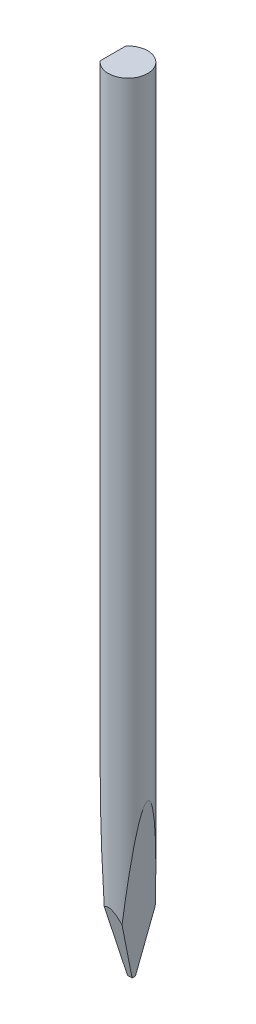
SolidWorks part; units mm, degrees
material "Tungsten"
ref_plane "Front Plane" through (0, 0, 0) normal (0, 0, 1) x (1, 0, 0)
ref_plane "Top Plane" through (0, 0, 0) normal (0, 1, 0) x (1, 0, 0)
ref_plane "Right Plane" through (0, 0, 0) normal (1, 0, 0) x (0, 0, -1)
sketch "TD_sketch" plane through (0, 0, 0) normal (0, 1, 0) x (1, 0, 0)
  circle A0 centre (0, 0) radius 1.5862
  dimension "TD" = 3.1725
extrude "TL_feature" add sketch "TD_sketch" along normal blind 63.5
sketch "TDF_sketch" plane through (0, 0, 0) normal (0, 1, 0) x (1, 0, 0)
  line L0 (-1.2078, 0) -> (1.5862, 0) construction
  line L1 (-1.2078, -1.5962) -> (-4.4002, -1.5962)
  line L2 (-1.2078, -1.5962) -> (-1.2078, 1.5962)
  line L3 (-1.2078, 1.5962) -> (-4.4002, 1.5962)
  line L4 (-4.4002, -1.5962) -> (-4.4002, 1.5962)
  line L5 (-1.2078, -1.5962) -> (-4.4002, 1.5962) construction
  line L6 (-1.2078, 1.5962) -> (-4.4002, -1.5962) construction
  circle A0 centre (0, 0) radius 1.5862 construction
  point P3 (-2.804, 0)
  dimension "TD" = 3.1725
  dimension "TDF" = 2.794
  dimension "Offset" = 3.1925
extrude "TDF_feature" cut sketch "TDF_sketch" along normal through all
sketch "ISA_sketch" plane through (0, 0, 0) normal (1, 0, 0) x (0, 0, -1)
  line L0 (-1.5862, 0) -> (1.5862, 0) construction
  line L1 (0, 0) -> (0, 63.5) construction
  line L2 (-0.1333, 0) -> (0.1333, 0)
  line L3 (0.1333, 0) -> (17.1481, 63.5)
  line L4 (-0.1333, 0) -> (-17.1481, 63.5)
  dimension "TD" = 3.1725
  dimension "TL" = 63.5
  dimension "W" = 0.2667
  dimension "ISA" = 30
extrude "ISA_feature" cut sketch "ISA_sketch" against normal through all both and the other way through all
sketch "VR_sketch" [suppressed] plane through (0, 0, 0) normal (1, 0, 0) x (0, 0, -1)
  line L0 (-1.5862, 0) -> (1.5862, 0) construction
  line L1 (0, 0) -> (0, 63.5) construction
  line L2 (-0.4483, 0) -> (0.4483, 0)
  line L3 (0.4483, 0) -> (0.4483, 1.016)
  line L4 (0.4855, 1.1058) -> (62.8797, 63.5)
  line L5 (-0.4855, 1.1058) -> (-62.8797, 63.5)
  line L6 (-0.4483, 0) -> (-0.4483, 1.016)
  arc A0 (0.4483, 1.016) -> (0.4855, 1.1058) centre (0.5753, 1.016) cw
  arc A1 (-0.4483, 1.016) -> (-0.4855, 1.1058) centre (-0.5753, 1.016) ccw
  dimension "TD" = 3.1725
  dimension "TL" = 63.5
  dimension "VRR" = 0.127
  dimension "VR" = 1.016
  dimension "VW" = 0.8966
  dimension "VRA" = 90
extrude "VR_feature" [suppressed] cut sketch "VR_sketch" against normal through all both and the other way through all
sketch "STD_shank_sketch" plane through (0, 0, 0) normal (0, 0, 1) x (1, 0, 0)
  line L0 (-1.5862, 0) -> (1.5862, 0) construction
  line L1 (-1.2078, 0) -> (-1.2078, 63.5) construction
  line L2 (0.4636, 0) -> (0.4636, 63.5) construction
  line L3 (0.4636, 0) -> (6.0191, 63.5)
  line L4 (0.4636, 0) -> (0.0953, 0)
  line L5 (0.0953, 0) -> (-5.4603, 63.5)
  dimension "TD" = 3.1725
  dimension "TL" = 63.5
  dimension "TDF" = 2.794
  dimension "X" = 1.1227
  dimension "BA" = 5
  dimension "FA" = 5
  dimension "FL" = 0.3683
extrude "STD_shank_feature" cut sketch "STD_shank_sketch" against normal through all both and the other way through all
sketch "VFL_sketch" [suppressed] plane through (0, 0, 0) normal (0, 0, 1) x (1, 0, 0)
  line L0 (-1.5862, 0) -> (1.5862, 0) construction
  line L1 (-1.2078, 0) -> (-1.2078, 63.5) construction
  line L2 (0.6083, 0) -> (0.6083, 63.5) construction
  line L3 (-0.2299, 0) -> (-0.2299, 1.905)
  line L4 (-0.2376, 1.9932) -> (-11.0829, 63.5)
  arc A0 (-0.2299, 1.905) -> (-0.2376, 1.9932) centre (-0.7379, 1.905) ccw
  dimension "TD" = 3.1725
  dimension "TL" = 63.5
  dimension "TDF" = 2.794
  dimension "X" = 1.1227
  dimension "FL" = 0.3683
  dimension "VFLR" = 0.508
  dimension "VFL" = 1.905
  dimension "angle" = 10
extrude "VFL_feature" [suppressed] cut sketch "VFL_sketch" against normal through all both and the other way through all
sketch "G_groove_sketch" [suppressed] plane through (0, 0, 0) normal (1, 0, 0) x (0, 0, -1)
  line L0 (-1.5862, 0) -> (1.5862, 0) construction
  line L1 (0, 0) -> (0, 63.5) construction
  line L2 (0.0229, 0.0689) -> (0.0711, 0)
  line L3 (0.0711, 0) -> (-0.0711, 0)
  line L4 (-0.0711, 0) -> (-0.0229, 0.0689)
  arc A0 (0.0229, 0.0689) -> (-0.0229, 0.0689) centre (0, 0.0529) ccw
  dimension "TD" = 3.1725
  dimension "TL" = 63.5
  dimension "GR" = 0.0279
  dimension "GA" = 70
  dimension "B" = 0.1422
extrude "G_groove_feature" [suppressed] cut sketch "G_groove_sketch" against normal through all both and the other way through all
sketch "FR_BR_STD_sketch" [suppressed] plane through (0, 0, 0) normal (0, 0, 1) x (1, 0, 0)
  line L0 (0.0953, 0) -> (-5.4603, 63.5) construction
  line L1 (0.4636, 0) -> (6.0191, 63.5) construction
  line L2 (0.1411, 0.0813) -> (0.3316, 0.0813)
  line L3 (-1.5862, 0) -> (1.5862, 0) construction
  arc A0 (0.0852, 0.1146) -> (0.1411, 0.0813) centre (0.1411, 0.1448) ccw
  arc A1 (0.484, 0.2337) -> (0.3316, 0.0813) centre (0.3316, 0.2337) cw
  dimension "BR" = 0.1524
  dimension "FR" = 0.0635
  dimension "GD" = 0.0813
  dimension "FRX" = 0.0559
  dimension "BRX" = 0.1524
surface "FR_BR_STD_feature" [suppressed]
sketch "G_groove_sketch<2>" [suppressed]
  dimension "TD" = 3.1725
  dimension "TL" = 63.5
  dimension "GR" = 0.0279
  dimension "GA" = 70
  dimension "B" = 0.1422
other "FR_BR_STD_cut_feature" [suppressed]
sketch "FR_BR_STD_VFL_sketch" [suppressed] plane through (0, 0, 0) normal (0, 0, 1) x (1, 0, 0)
  line L0 (-0.2299, 0) -> (-0.2299, 1.905) construction
  line L2 (0.2781, 0.3734) -> (0.1774, 0.3734)
  line L3 (0.6083, 0) -> (6.1639, 63.5) construction
  line L4 (0.6083, 0) -> (-0.2299, 0) construction
  arc A0 (-0.2299, 0.8814) -> (0.2781, 0.3734) centre (0.2781, 0.8814) ccw
  arc A1 (0.1774, 0.3734) -> (0.6854, 0.8814) centre (0.1774, 0.8814) ccw
  dimension "BR" = 0.1524
  dimension "FR" = 0.0635
  dimension "GD" = 0.0813
  dimension "FRX" = 0.0559
  dimension "BRX" = 0.1524
surface "FR_BR_STD_VFL_feature" [suppressed]
sketch "G_groove_sketch<3>" [suppressed]
  dimension "TD" = 3.1725
  dimension "TL" = 63.5
  dimension "GR" = 0.0279
  dimension "GA" = 70
  dimension "B" = 0.1422
other "FR_BR_STD_VFL_cut_feature" [suppressed]
sketch "FL_STD_sketch" [suppressed] plane through (0, 0, 0) normal (0, 0, 1) x (1, 0, 0)
  line L0 (0.0953, 0) -> (-5.4603, 63.5) construction
  line L1 (0.4636, 0) -> (6.0191, 63.5) construction
  line L2 (0.1411, 0.0813) -> (0.3316, 0.0813)
  line L3 (0.4636, 0) -> (0.0953, 0) construction
  arc A0 (0.0852, 0.1146) -> (0.1411, 0.0813) centre (0.1411, 0.1448) ccw
  arc A1 (0.484, 0.2337) -> (0.3316, 0.0813) centre (0.3316, 0.2337) cw
  dimension "BR" = 0.1524
  dimension "FR" = 0.0635
  dimension "GD" = 0.0813
  dimension "FRX" = 0.0559
  dimension "BRX" = 0.1524
sketch "FL_STD_VFL_sketch" [suppressed] plane through (0, 0, 0) normal (0, 0, 1) x (1, 0, 0)
  line L0 (-0.2299, 0) -> (-0.2299, 1.905) construction
  line L1 (0.6083, 0) -> (6.1639, 63.5) construction
  line L2 (0.2781, 0.3734) -> (0.1774, 0.3734)
  line L3 (-1.5862, 0) -> (1.5862, 0) construction
  arc A0 (-0.2299, 0.8814) -> (0.2781, 0.3734) centre (0.2781, 0.8814) ccw
  arc A1 (0.6854, 0.8814) -> (0.1774, 0.3734) centre (0.1774, 0.8814) cw
  dimension "BR" = 0.1524
  dimension "FR" = 0.0635
  dimension "GD" = 0.0813
  dimension "FRX" = 0.0559
  dimension "BRX" = 0.1524
sketch "TIP_sketch" [suppressed] plane through (0, 0, 0) normal (0, 0, 1) x (1, 0, 0)
  line L0 (-0.0113, 0.0339) -> (0.0321, 0.0339)
  line L1 (-0.0083, 0) -> (-0.2271, 2.5) construction
  line L2 (0.0291, 0) -> (0.2479, 2.5) construction
  line L3 (0.0291, 0) -> (-0.0083, 0) construction
  dimension "TIP" = 0.0339
sketch "ref_point" [suppressed] plane through (0, 0, 0) normal (1, 0, 0) x (0, 0, -1)
  point P0 (0, 0.2792)
  dimension "ref_point" = 0.2792
ref_plane "H_cut_plan" [suppressed] through (0, 0.2792, 0) normal (0, 1, 0) x (1, 0, 0)
other "H_cut_feature" [suppressed]
sketch "FG_FL_STD_overlay_sketch" [suppressed] plane through (0, 0, 0) normal (0, 0, 1) x (1, 0, 0)
  line L0 (0.4636, 0) -> (6.0191, 63.5) construction
  line L1 (0.4636, 0) -> (0.0953, 0) construction
  line L2 (0.0953, 0) -> (-5.4603, 63.5) construction
  line L3 (0.4636, 0) -> (0.488, 0.2792)
  line L4 (0.4636, 0) -> (0.0953, 0)
  line L5 (0.0953, 0) -> (0.0708, 0.2792)
  line L6 (0.0708, 0.2792) -> (0.488, 0.2792)
  line L7 (0.0406, 0.2792) -> (-0.0406, 0.2792) construction
  line L8 (0.4645, -0.0001) -> (0.489, 0.2791)
  line L9 (0.4626, 0.0001) -> (0.487, 0.2793)
  dimension "FL_UTOL" = 0.001
  dimension "FL_LTOL" = 0.001
sketch "FG_FL_STD_VFL_overlay_sketch" [suppressed] plane through (0, 0, 0) normal (0, 0, 1) x (1, 0, 0)
  line L0 (-0.0087, 0.0785) -> (-0.4356, 2.5) construction
  line L1 (0.0291, 0) -> (0.2479, 2.5) construction
  line L2 (0.0291, 0) -> (-0.0083, 0) construction
  line L3 (-0.0083, 0) -> (-0.0083, 0.075) construction
  line L4 (-0.0087, 0.0785) -> (-0.0314, 0.2077)
  line L5 (0.0291, 0) -> (0.0473, 0.2077)
  line L6 (0.0291, 0) -> (-0.0083, 0)
  line L7 (-0.0083, 0) -> (-0.0083, 0.075)
  line L8 (-0.0314, 0.2077) -> (0.0473, 0.2077)
  line L9 (0.0687, 0.2077) -> (-0.0687, 0.2077) construction
  line L10 (0.0301, -0.0001) -> (0.0483, 0.2076)
  line L11 (0.0282, 0.0001) -> (0.0463, 0.2078)
  arc A0 (-0.0083, 0.075) -> (-0.0087, 0.0785) centre (-0.0284, 0.075) ccw construction
  arc A1 (-0.0083, 0.075) -> (-0.0087, 0.0785) centre (-0.0284, 0.075) ccw
  dimension "FL_UTOL" = 0.001
  dimension "FL_LTOL" = 0.001
sketch "FG_B_STD_overlay_sketch" [suppressed] plane through (0, 0, 0) normal (1, 0, 0) x (0, 0, -1)
  line L0 (0.1333, 0) -> (17.1481, 63.5) construction
  line L1 (-0.1333, 0) -> (0.1333, 0) construction
  line L2 (-0.1333, 0) -> (-17.1481, 63.5) construction
  line L3 (0.1333, 0) -> (0.2082, 0.2792)
  line L4 (-0.1333, 0) -> (-0.0699, 0)
  line L5 (-0.1333, 0) -> (-0.2082, 0.2792)
  line L8 (0.0699, 0) -> (0.1333, 0)
  line L9 (-0.2082, 0.2792) -> (0.2082, 0.2792)
  line L10 (0.0221, 0.0683) -> (0.0703, -0.0006)
  line L11 (-0.0703, -0.0006) -> (-0.0221, 0.0683)
  line L12 (0.0221, 0.0683) -> (0.0699, 0)
  line L13 (-0.0699, 0) -> (-0.0221, 0.0683)
  line L14 (0.0237, 0.0695) -> (0.0719, 0.0006)
  line L15 (-0.0719, 0.0006) -> (-0.0237, 0.0695)
  line L16 (0.0237, 0.0695) -> (0.0723, 0)
  line L17 (-0.0723, 0) -> (-0.0237, 0.0695)
  line L18 (0.0406, 0.2792) -> (-0.0406, 0.2792) construction
  line L19 (-0.1324, 0.0003) -> (-0.2072, 0.2795)
  line L20 (-0.1343, -0.0003) -> (-0.2091, 0.279)
  arc A2 (0.0221, 0.0683) -> (-0.0221, 0.0683) centre (0, 0.0529) ccw
  arc A3 (0.0221, 0.0683) -> (-0.0221, 0.0683) centre (0, 0.0529) ccw
  arc A4 (0.0237, 0.0695) -> (-0.0237, 0.0695) centre (0, 0.0529) ccw
  arc A5 (0.0237, 0.0695) -> (-0.0237, 0.0695) centre (0, 0.0529) ccw
  ellipse E0 centre (1.3138, -1.5083) end of major axis (2.5414, -3.248) minor radius 0.1522 (0.105, 0.1264) -> (0.1442, 0.0406) ccw construction
  ellipse E1 centre (-1.3138, -1.5083) end of major axis (-0.0863, 0.2315) minor radius 0.1522 (-0.1442, 0.0406) -> (-0.105, 0.1264) ccw construction
  ellipse E2 centre (1.3138, -1.5083) end of major axis (2.5414, -3.248) minor radius 0.1522 (0.105, 0.1264) -> (0.1442, 0.0406) ccw
  ellipse E3 centre (-1.3138, -1.5083) end of major axis (-0.0863, 0.2315) minor radius 0.1522 (-0.1442, 0.0406) -> (-0.105, 0.1264) ccw
  spline S0 degree 3 poles (1644.6812, -1137.5783) (-11.5572, -22.4368) (-1.1514, 0.547) (0.0233, 0.2038) (0.035, 0.2004) (0.0462, 0.1946) (0.0562, 0.1876) (0.0688, 0.1788) (0.0799, 0.1677) (0.0889, 0.1552) (1.1453, -1.3082) (-25.0391, -24.8112) (-1139.1293, 1643.7059) knots -0.003641 -0.003641 -0.003641 -0.003641 0.000029 0.000029 0.000029 0.000066 0.000066 0.000066 0.000112 0.000112 0.000112 0.005548 0.005548 0.005548 0.005548 only from (0, 0.2072) to (0.105, 0.1264) construction
  spline S1 degree 3 poles (1108.6293, 1664.4054) (26.4709, -22.8226) (-1.0637, -1.3693) (-0.0934, 0.1486) (-0.085, 0.1618) (-0.0743, 0.1737) (-0.062, 0.1833) (-0.052, 0.1911) (-0.0408, 0.1977) (-0.0289, 0.202) (-0.02, 0.2051) (-0.0106, 0.2071) (-0.0012, 0.2072) (1.2104, 0.2251) (2.9491, -28.0575) (-1994.1481, -150.3085) knots -0.005313 -0.005313 -0.005313 -0.005313 0.000089 0.000089 0.000089 0.000136 0.000136 0.000136 0.000174 0.000174 0.000174 0.000202 0.000202 0.000202 0.00377 0.00377 0.00377 0.00377 only from (-0.105, 0.1264) to (0, 0.2072) construction
  spline S2 degree 3 poles (0, 0.2072) (0.0079, 0.2072) (0.0158, 0.206) (0.035, 0.2004) (0.0462, 0.1946) (0.0562, 0.1876) (0.0688, 0.1788) (0.0799, 0.1677) (0.0889, 0.1552) (0.0954, 0.1463) (0.1008, 0.1365) (0.105, 0.1264) knots 0.000005 0.000005 0.000005 0.000005 0.000029 0.000029 0.000066 0.000066 0.000066 0.000112 0.000112 0.000112 0.000145 0.000145 0.000145 0.000145
  spline S3 degree 3 poles (-0.105, 0.1264) (-0.1018, 0.1341) (-0.0979, 0.1416) (-0.0934, 0.1486) (-0.085, 0.1618) (-0.0743, 0.1737) (-0.062, 0.1833) (-0.052, 0.1911) (-0.0408, 0.1977) (-0.0289, 0.202) (-0.02, 0.2051) (-0.0106, 0.2071) (-0.0012, 0.2072) (-0.0008, 0.2072) (-0.0004, 0.2072) (0, 0.2072) knots 0.000064 0.000064 0.000064 0.000064 0.000089 0.000089 0.000089 0.000136 0.000136 0.000136 0.000174 0.000174 0.000174 0.000202 0.000202 0.000202 0.000203 0.000203 0.000203 0.000203
  dimension "B_UTOL" = 0.001
  dimension "B_LTOL" = 0.001
  dimension "W_UTOL" = 0.001
  dimension "W_LTOL" = 0.001
sketch "FG_B_STD_VR_overlay_sketch" [suppressed] plane through (0, 0, 0) normal (1, 0, 0) x (0, 0, -1)
  line L0 (-0.2413, 0) -> (0.2413, 0) construction
  line L1 (-0.2413, 0) -> (-0.2413, 0.6096) construction
  line L2 (-0.276, 0.6662) -> (-123.5943, 63.5) construction
  line L3 (0.276, 0.6662) -> (123.5943, 63.5) construction
  line L4 (0.2413, 0) -> (0.2413, 0.6096) construction
  line L5 (-0.2413, 0) -> (-0.1842, 0)
  line L6 (-0.2413, 0) -> (-0.2413, 0.6096)
  line L7 (-0.276, 0.6662) -> (-0.618, 0.8404)
  line L8 (0.276, 0.6662) -> (0.618, 0.8404)
  line L9 (0.2413, 0) -> (0.2413, 0.6096)
  line L10 (-0.618, 0.8404) -> (0.618, 0.8404)
  line L11 (0.0406, 0.8404) -> (-0.0406, 0.8404) construction
  line L17 (-1.5862, 0) -> (1.5862, 0) construction
  line L18 (0.1842, 0) -> (0.2413, 0)
  line L19 (0.0678, 0.1662) -> (0.1846, -0.0006)
  line L20 (-0.1846, -0.0006) -> (-0.0678, 0.1662)
  line L21 (0.0678, 0.1662) -> (0.1842, 0)
  line L22 (-0.1842, 0) -> (-0.0678, 0.1662)
  line L23 (0.0695, 0.1673) -> (0.1862, 0.0006)
  line L24 (-0.1862, 0.0006) -> (-0.0695, 0.1673)
  line L25 (0.0695, 0.1673) -> (0.1866, 0)
  line L26 (-0.1866, 0) -> (-0.0695, 0.1673)
  arc A0 (-0.2413, 0.6096) -> (-0.276, 0.6662) centre (-0.3048, 0.6096) ccw construction
  arc A1 (0.276, 0.6662) -> (0.2413, 0.6096) centre (0.3048, 0.6096) ccw construction
  arc A2 (-0.2413, 0.6096) -> (-0.276, 0.6662) centre (-0.3048, 0.6096) ccw
  arc A3 (0.276, 0.6662) -> (0.2413, 0.6096) centre (0.3048, 0.6096) ccw
  arc A7 (0.0678, 0.1662) -> (-0.0678, 0.1662) centre (0, 0.1187) ccw
  arc A8 (0.0678, 0.1662) -> (-0.0678, 0.1662) centre (0, 0.1187) ccw
  arc A9 (0.0695, 0.1673) -> (-0.0695, 0.1673) centre (0, 0.1187) ccw
  arc A10 (0.0695, 0.1673) -> (-0.0695, 0.1673) centre (0, 0.1187) ccw
  dimension "B_LTOL" = 0.001
  dimension "B_UTOL" = 0.001
sketch "PGB_FL_overlay_sketch" [suppressed] plane through (0, 0, 0) normal (0, 0, 1) x (1, 0, 0)
  line L0 (0.0953, 0) -> (-5.4603, 63.5) construction
  line L1 (0.4636, 0) -> (0.0953, 0) construction
  line L2 (0.4636, 0) -> (6.0191, 63.5) construction
  line L3 (0.0953, 0) -> (0.0583, 0.422)
  line L4 (0.4636, 0) -> (0.0953, 0)
  line L5 (0.4636, 0) -> (0.5005, 0.422)
  line L6 (0.0583, 0.422) -> (0.5005, 0.422)
  line L7 (0.0406, 0.422) -> (-0.0406, 0.422) construction
  line L8 (0.4645, -0.0001) -> (0.5015, 0.4219)
  line L9 (0.4626, 0.0001) -> (0.4995, 0.422)
  dimension "FL_UTOL" = 0.001
  dimension "FL_LTOL" = 0.001
sketch "PGB_W_overlay_sketch" [suppressed] plane through (0, 0, 0) normal (1, 0, 0) x (0, 0, -1)
  line L0 (-0.1333, 0) -> (-17.1481, 63.5) construction
  line L1 (-0.1333, 0) -> (0.1333, 0) construction
  line L2 (0.1333, 0) -> (17.1481, 63.5) construction
  line L3 (-0.1333, 0) -> (-0.2464, 0.422)
  line L4 (-0.1333, 0) -> (0.1333, 0)
  line L5 (0.1333, 0) -> (0.2464, 0.422)
  line L6 (-0.2464, 0.422) -> (0.2464, 0.422)
  line L7 (0.0406, 0.422) -> (-0.0406, 0.422) construction
  line L8 (-0.1324, 0.0003) -> (-0.2454, 0.4222)
  line L9 (-0.1343, -0.0003) -> (-0.2474, 0.4217)
  dimension "W_LTOL" = 0.001
  dimension "W_UTOL" = 0.001
equation "\"TD\"=3.17246"
equation "\"TD@TD_sketch\" = \"TD\""
equation "\"TL@TL_feature\"=\"TL\""
equation "\"TD@TDF_sketch\" = \"TD\""
equation "\"TDF\"=2.794"
equation "\"TDF@TDF_sketch\" = \"TDF\""
equation "\"_offset\"= 0.01"
equation "\"Offset@TDF_sketch\" = \"TD\" + \"_offset\" * 2"
equation "\"TD@ISA_sketch\" = \"TD\""
equation "\"TL\"=63.5"
equation "\"TL@ISA_sketch\" = \"TL\""
equation "\"W\"=0.2667"
equation "\"W@ISA_sketch\" = \"W\""
equation "\"ISA\"=30"
equation "\"ISA@ISA_sketch\" = \"ISA\""
equation "\"TD@VR_sketch\" = \"TD\""
equation "\"TL@VR_sketch\" = \"TL\""
equation "\"VR\"=1.016"
equation "\"VW\"=0.89662"
equation "\"VW@VR_sketch\" = \"VW\""
equation "\"VRR\"=0.127"
equation "\"VRR@VR_sketch\" = \"VRR\""
equation "\"VRA\"=90"
equation "\"VRA@VR_sketch\" = \"VRA\""
equation "\"TD@STD_shank_sketch\" = \"TD\""
equation "\"TL@STD_shank_sketch\" = \"TL\""
equation "\"TDF@STD_shank_sketch\" = \"TDF\""
equation "\"X\"=1.12268"
equation "\"X@STD_shank_sketch\" = \"X\""
equation "\"BA\"=5"
equation "\"BA@STD_shank_sketch\" = \"BA\""
equation "\"FA\"=5"
equation "\"FA@STD_shank_sketch\" = \"FA\""
equation "\"FL\"=0.3683"
equation "\"FL@STD_shank_sketch\" = \"FL\""
equation "\"TL@VFL_sketch\" = \"TL\""
equation "\"TD@VFL_sketch\" = \"TD\""
equation "\"TDF@VFL_sketch\" = \"TDF\""
equation "\"X@VFL_sketch\" = \"X\""
equation "\"FL@VFL_sketch\" = \"FL\""
equation "\"VFL\"=1.905"
equation "\"VFL@VFL_sketch\" = \"VFL\""
equation "\"VFLR\"=0.508"
equation "\"VFLR@VFL_sketch\" = \"VFLR\""
equation "\"TD@G_groove_sketch\" = \"TD\""
equation "\"TL@G_groove_sketch\" = \"TL\""
equation "\"GA\"=70"
equation "\"GA@G_groove_sketch\" = \"GA\""
equation "\"B\"=0.14224"
equation "\"B@G_groove_sketch\" = \"B\""
equation "\"GR\"=0.02794"
equation "\"GR@G_groove_sketch\" = \"GR\""
equation "\"FR\"=0.0635"
equation "\"FR@FR_STD_feature\"=\"FR\""
equation "\"BR\"=0.1524"
equation "\"FR@FR_STD_VFL_feature\"=\"FR\""
equation "\"BR@BR_STD_feature\"=\"BR\""
equation "\"BR@BR_STD_VFL_feature\"=\"BR\""
equation "\"GD\"=0.08128"
equation "\"GD@FR_BR_STD_sketch\" = \"GD\""
equation "\"BR@FR_BR_STD_sketch\" = \"BR\""
equation "\"FR@FR_BR_STD_sketch\" = \"FR\""
equation "\"FRX\"=0.05588"
equation "\"FRX@FR_BR_STD_sketch\" = \"FRX\""
equation "\"BRX\"=0.1524"
equation "\"BRX@FR_BR_STD_sketch\" = \"BRX\""
equation "\"FR@FR_BR_STD_VFL_sketch\" = \"FR\""
equation "\"BR@FR_BR_STD_VFL_sketch\" = \"BR\""
equation "\"GD@FR_BR_STD_VFL_sketch\" = \"GD\""
equation "\"FRX@FR_BR_STD_VFL_sketch\" = \"FRX\""
equation "\"BRX@FR_BR_STD_VFL_sketch\" = \"BRX\""
equation "\"FR@FL_STD_sketch\" = \"FR\""
equation "\"BR@FL_STD_sketch\" = \"BR\""
equation "\"BRX@FL_STD_sketch\" = \"BRX\""
equation "\"FRX@FL_STD_sketch\" = \"FRX\""
equation "\"GD@FL_STD_sketch\" = \"GD\""
equation "\"FR@FL_STD_VFL_sketch\" = \"FR\""
equation "\"BR@FL_STD_VFL_sketch\" = \"BR\""
equation "\"BRX@FL_STD_VFL_sketch\" = \"BRX\""
equation "\"FRX@FL_STD_VFL_sketch\" = \"FRX\""
equation "\"GD@FL_STD_VFL_sketch\" = \"GD\""
equation "\"TIP\"=0.0338712"
equation "\"TIP@TIP_sketch\" = \"TIP\""
equation "\"scale\"=183"
equation "\"ref_point@ref_point\"=2.01175in / \"scale\""
equation "\"VR_LTOL\"=0.0762"
equation "\"VR_UTOL\"=0.0762"
equation "\"B_LTOL\"=0.00762"
equation "\"B_UTOL\"=0.00762"
equation "\"VR@VR_sketch\"=\"VR\""
equation "\"FL_LTOL\"=0.0127"
equation "\"FL_UTOL\"=0.0127"
equation "\"F\"=0.1778"
